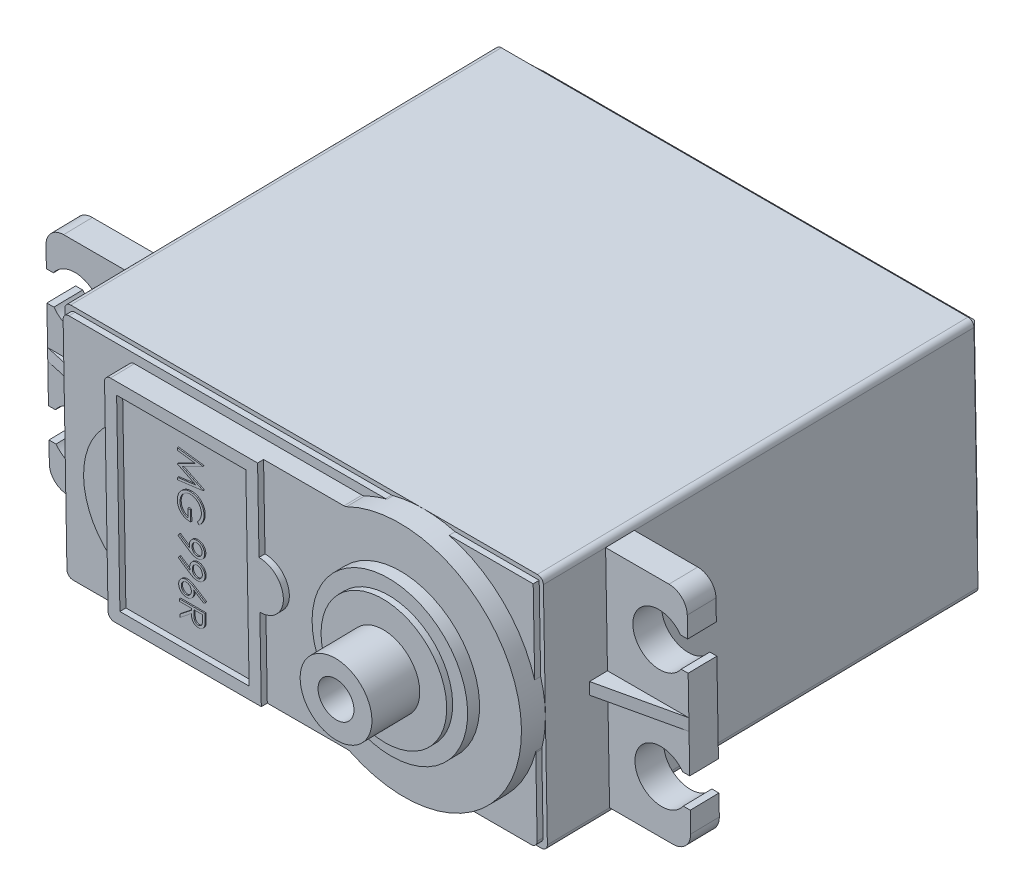
SolidWorks part; units mm, degrees
ref_plane "Front Plane" through (0, 0, 0) normal (0, 0, 1) x (1, 0, 0)
ref_plane "Top Plane" through (0, 0, 0) normal (0, 1, 0) x (1, 0, 0)
ref_plane "Right Plane" through (0, 0, 0) normal (1, 0, 0) x (0, 0, -1)
sketch "Sketch2" plane through (0, 0, 0) normal (0, 1, 0) x (1, 0, 0)
  line L1 (-20, 10) -> (20, 10)
  line L2 (-20, 10) -> (-20, -10)
  line L3 (-20, -10) -> (20, -10)
  line L4 (20, 10) -> (20, -10)
  line L5 (-20, 10) -> (20, -10) construction
  line L6 (-20, -10) -> (20, 10) construction
  point P0 (0, 0)
  dimension "D1" = 40
  dimension "0" = 20
extrude "Boss-Extrude1" add sketch "Sketch2" along normal blind 38
sketch "Sketch3" plane through (0, 38, 0) normal (0, 1, 0) x (1, 0, 0)
  line L0 (0, 0) -> (20, 0) construction
  line L1 (20, -10) -> (20, 10) construction
  line L2 (20, 10) -> (-20, 10) construction
  line L3 (0, 0) -> (-20, 0) construction
  line L4 (-20, 10) -> (-20, -10) construction
  line L6 (-14.2, -8.9) -> (5.4404, -8.9)
  line L7 (-14.2, -8.9) -> (-14.2, 8.9)
  line L8 (-14.2, 8.9) -> (5.4404, 8.9)
  line L9 (5.4404, -8.9) -> (5.4404, 8.9)
  line L10 (-14.2, -8.9) -> (5.4404, 8.9) construction
  line L11 (-14.2, 8.9) -> (5.4404, -8.9) construction
  circle A0 centre (10, 0) radius 10
  circle A1 centre (-10.1917, 0) radius 6.4083
  point P12 (-4.3798, 0)
  point P17 (-16.6, 0)
  point P21 (-14.2, 5)
  dimension "D1" = 5.8
  dimension "D2" = 17.8
  dimension "D3" = 3.4
  dimension "D4" = 5
extrude "Boss-Extrude2" add sketch "Sketch3" along normal blind 2 contours A0 L9 | L9 A0 | A1 L7 L6 A0 L8 | L7 A1 | L7 A1
sketch "Sketch4" plane through (0, 38, 0) normal (0, 1, 0) x (1, 0, 0)
  line L14 (-19.65, 9.65) -> (-19.65, -9.65)
  line L15 (-19.65, -9.65) -> (10, -9.65)
  line L16 (10, -9.65) -> (19.65, -9.65)
  line L17 (19.65, -9.65) -> (19.65, 0)
  line L18 (19.65, 0) -> (19.65, 9.65)
  line L19 (19.65, 9.65) -> (10, 9.65)
  line L20 (10, 9.65) -> (-19.65, 9.65)
  line L21 (-19.65, 9.65) -> (-19.65, -9.65)
  line L22 (-19.65, -9.65) -> (10, -9.65)
  line L23 (10, -9.65) -> (19.65, -9.65)
  line L24 (19.65, -9.65) -> (19.65, 0)
  line L25 (19.65, 0) -> (19.65, 9.65)
  line L26 (19.65, 9.65) -> (10, 9.65)
  line L27 (10, 9.65) -> (-19.65, 9.65)
  dimension "D1" = 0.35
extrude "Boss-Extrude3" add sketch "Sketch4" along normal blind 0.5
sketch "Sketch5" plane through (0, 40, 0) normal (0, 1, 0) x (1, 0, 0)
  line L0 (-14.2, -8.9) -> (5.4404, -8.9) construction
  line L1 (-14.2, 8.9) -> (-1.4, 8.9)
  line L2 (-14.2, 8.9) -> (-14.2, -8.9)
  line L3 (-14.2, -8.9) -> (-1.4, -8.9)
  line L4 (-1.4, 8.9) -> (-1.4, -8.9)
  line L5 (-14.2, 8.9) -> (-1.4, -8.9) construction
  line L7 (-13.2, -7.9) -> (-2.4, -7.9)
  line L8 (-13.2, -7.9) -> (-13.2, 7.9)
  line L9 (-13.2, 7.9) -> (-2.4, 7.9)
  line L10 (-2.4, -7.9) -> (-2.4, 7.9)
  line L11 (-13.2, -7.9) -> (-2.4, 7.9) construction
  line L12 (-13.2, 7.9) -> (-2.4, -7.9) construction
  point P7 (-7.8, 0)
  dimension "D1" = 12.8
  dimension "D2" = 1
  dimension "D3" = 1
extrude "Boss-Extrude4" add sketch "Sketch5" along normal blind 0.5
sketch "Sketch6" plane through (0, 40, 0) normal (0, 1, 0) x (1, 0, 0)
  line L0 (0, 0) -> (-19.65, 0) construction
  line L1 (-19.65, 9.65) -> (-19.65, -9.65) construction
  line L2 (-1.4, -8.9) -> (-1.4, 8.9) construction
  line L3 (-1.4, 2) -> (-1.4, -2)
  circle A0 centre (-1.4, 0) radius 2
  dimension "D1" = 4
extrude "Boss-Extrude5" add sketch "Sketch6" along normal blind 0.5
sketch "Sketch7" plane through (0, 40, 0) normal (0, 1, 0) x (1, 0, 0)
  circle A0 centre (10, 0) radius 6.5
  dimension "D1" = 13
extrude "Boss-Extrude6" add sketch "Sketch7" along normal blind 1
sketch "Sketch8" plane through (0, 41, 0) normal (0, 1, 0) x (1, 0, 0)
  circle A0 centre (10, 0) radius 5.25
  dimension "D1" = 10.5
extrude "Boss-Extrude7" add sketch "Sketch8" along normal blind 0.5
sketch "Sketch9" plane through (0, 41.5, 0) normal (0, 1, 0) x (1, 0, 0)
  circle A0 centre (10, 0) radius 3
  dimension "D1" = 6
extrude "Boss-Extrude8" add sketch "Sketch9" along normal blind 4
sketch "Sketch10" plane through (0, 45.5, 0) normal (0, 1, 0) x (1, 0, 0)
  circle A0 centre (10, 0) radius 1.5
  dimension "D1" = 3
extrude "Cut-Extrude1" cut sketch "Sketch10" against normal blind 10
chamfer "Chamfer1" distance 2 angle 45 4 edges at (20, 0, 0) (0, 0, -10) (-20, 0, 0) (0, 0, 10)
sketch "Sketch11" plane through (0, 0, 0) normal (0, -1, 0) x (1, 0, 0)
  line L0 (0, 0) -> (0, 10) construction
  line L1 (-20, 10) -> (20, 10) construction
  line L2 (0, 0) -> (20, 0) construction
  circle A0 centre (-20, 10) radius 2.8284
  circle A1 centre (20, 10) radius 2.8284
  circle A2 centre (20, -10) radius 2.8284
  circle A3 centre (-20, -10) radius 2.8284
extrude "Cut-Extrude2" cut sketch "Sketch11" against normal blind 2
ref_plane "Plane4" through (0, 32.8, 0) normal (0, 1, 0) x (1, 0, 0)
fillet "Fillet1" radius 0.5 4 edges at (-20, 20, -10) (-20, 20, 10) (20, 20, -10) (20, 20, 10)
fillet "Fillet2" radius 0.5 13 edges at (5.4404, 39.25, -8.9) (-14.2, 39.5, -8.9) (-14.2, 39.25, -5) (-14.2, 39.25, 5) (-14.2, 39.5, 8.9) (-19.65, 38.25, 9.65) (-19.65, 38.25, -9.65) (7.3775, 38.25, -9.65) (5.4404, 39.25, 8.9) (12.6225, 38.25, 9.65) (7.3775, 38.25, 9.65) (19.65, 38.25, 2.6225) (19.65, 38.25, 9.65)
sketch "Sketch13" plane through (0, 32.8, 0) normal (0, 1, 0) x (1, 0, 0)
  line L0 (26.8, 0) -> (20, 0) construction
  line L1 (20, 9.5) -> (26.8, 9.5)
  line L2 (20, 9.5) -> (20, -9.5)
  line L3 (20, -9.5) -> (26.8, -9.5)
  line L4 (26.8, 9.5) -> (26.8, -9.5)
  line L5 (24.4, -5) -> (24.4, 5)
  line L6 (24.4, 5) -> (26.8, 5) construction
  line L7 (29.2, -6.25) -> (24.4, -6.25)
  line L8 (29.2, 3.75) -> (24.4, 3.75)
  line L9 (29.2, 3.75) -> (29.2, 6.25)
  line L10 (29.2, 6.25) -> (24.4, 6.25)
  line L11 (24.4, 3.75) -> (24.4, 6.25)
  line L12 (29.2, 3.75) -> (24.4, 6.25) construction
  line L13 (29.2, 6.25) -> (24.4, 3.75) construction
  line L14 (24.4, -3.75) -> (24.4, -6.25)
  line L15 (29.2, -3.75) -> (24.4, -3.75)
  line L16 (29.2, -3.75) -> (29.2, -6.25)
  line L17 (0, 0) -> (0, 10) construction
  line L18 (10, 10) -> (-19.5, 10) construction
  line L19 (-29.2, 6.25) -> (-24.4, 3.75) construction
  line L20 (-29.2, 3.75) -> (-24.4, 6.25) construction
  line L21 (-24.4, 5) -> (-26.8, 5) construction
  line L22 (-26.8, 0) -> (-20, 0) construction
  line L23 (-29.2, -3.75) -> (-29.2, -6.25)
  line L24 (-29.2, -3.75) -> (-24.4, -3.75)
  line L25 (-24.4, -3.75) -> (-24.4, -6.25)
  line L26 (-24.4, 3.75) -> (-24.4, 6.25)
  line L27 (-29.2, 6.25) -> (-24.4, 6.25)
  line L28 (-29.2, 3.75) -> (-29.2, 6.25)
  line L29 (-29.2, 3.75) -> (-24.4, 3.75)
  line L30 (-29.2, -6.25) -> (-24.4, -6.25)
  line L31 (-24.4, -5) -> (-24.4, 5)
  line L32 (-26.8, 9.5) -> (-26.8, -9.5)
  line L33 (-20, -9.5) -> (-26.8, -9.5)
  line L34 (-20, 9.5) -> (-20, -9.5)
  line L35 (-20, 9.5) -> (-26.8, 9.5)
  circle A0 centre (24.4, 5) radius 2.2
  circle A1 centre (24.4, -5) radius 2.2
  circle A2 centre (-24.4, -5) radius 2.2
  circle A3 centre (-24.4, 5) radius 2.2
  point P11 (24.4, 0)
  point P46 (-24.4, 0)
  dimension "D3" = 4.4
  dimension "D1" = 6.8
  dimension "D2" = 10
  dimension "D4" = 2.4
  dimension "D5" = 2.5
extrude "Boss-Extrude9" add sketch "Sketch13" against normal blind 2.4 contours L27 A3 L31 A2 L30 L32 L33 L34 L35 | L31 A3 L29 L32 L24 A2 | A1 L5 A0 L10 L4 L1 L2 L3 L7 | A1 L15 L4 L8 A0 L5
sketch "Sketch14" plane through (0, 0, 0) normal (0, 0, 1) x (1, 0, 0)
  line L0 (20, 34.3) -> (26.8, 32.8)
  line L1 (20, 38) -> (20, 32.8) construction
  line L2 (20, 32.8) -> (26.8, 32.8) construction
  line L3 (20, 34.3) -> (20, 32.8)
  line L4 (20, 32.8) -> (26.8, 32.8)
  line L5 (0, 0) -> (0, 36.6111) construction
  line L6 (-20, 32.8) -> (-26.8, 32.8)
  line L7 (-20, 34.3) -> (-20, 32.8)
  line L8 (-20, 34.3) -> (-26.8, 32.8)
  dimension "D1" = 1.5
extrude "Boss-Extrude10" add sketch "Sketch14" along normal blind 0.5 and the other way blind 0.5
sketch "Sketch15" plane through (0, 40, 0) normal (0, 1, 0) x (1, 0, 0)
  line L0 (-8.5615, 7.9) -> (-8.5615, -7.9) construction
  line L1 (-2.4, 7.9) -> (-13.2, 7.9) construction
  line L2 (-13.2, -7.9) -> (-2.4, -7.9) construction
  text T0 "MG 996R" font "Century Gothic" height in points 8
extrude "Boss-Extrude11" add sketch "Sketch15" along normal blind 0.1
fillet "Fillet3" radius 1.5 4 edges at (-26.8, 31.6, -9.5) (-26.8, 31.6, 9.5) (26.8, 31.6, -9.5) (26.8, 31.6, 9.5)
move or copy body "Body-Move/Copy1" bodies to move or copy 113 copy no rotation origin (0, 22.75, 0) rotation axis (1, 0, 0) rotation angle 91
